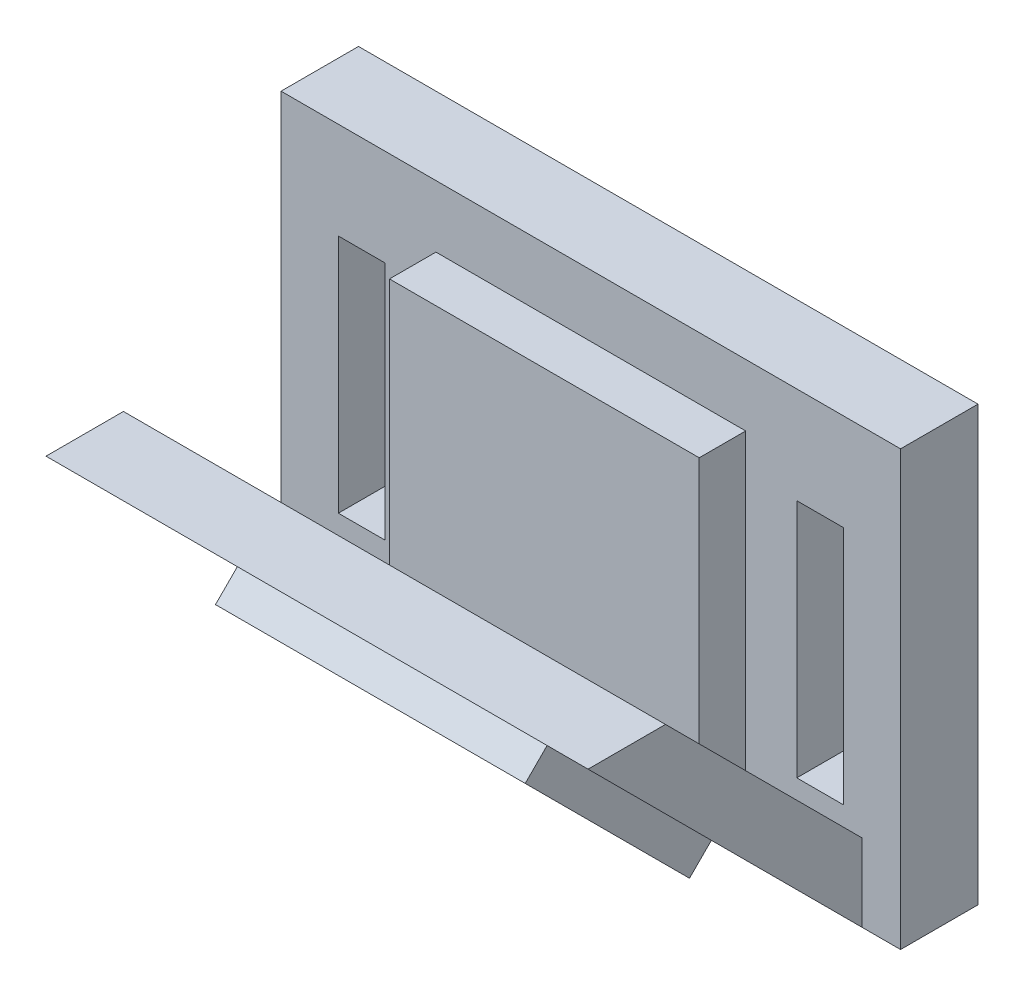
SolidWorks part; units mm, degrees
ref_plane "Alzado" through (0, 0, 0) normal (0, 0, 1) x (1, 0, 0)
ref_plane "Planta" through (0, 0, 0) normal (0, 1, 0) x (1, 0, 0)
ref_plane "Vista lateral" through (0, 0, 0) normal (1, 0, 0) x (0, 0, -1)
sketch "Croquis1" plane through (0, 0, 0) normal (0, 0, 1) x (1, 0, 0)
  line L0 (-39.1455, 0) -> (34.6181, 0) construction
  line L1 (-20, -14) -> (20, -14)
  line L2 (-20, -14) -> (-20, 14)
  line L3 (-20, 14) -> (20, 14)
  line L4 (20, -14) -> (20, 14)
  line L5 (-20, -14) -> (20, 14) construction
  line L6 (-20, 14) -> (20, -14) construction
  line L7 (0, 15.7634) -> (0, -15.7728) construction
  line L8 (13.3, -7.75) -> (16.3, -7.75)
  line L9 (13.3, -7.75) -> (13.3, 7.75)
  line L10 (13.3, 7.75) -> (16.3, 7.75)
  line L11 (16.3, -7.75) -> (16.3, 7.75)
  line L12 (13.3, -7.75) -> (16.3, 7.75) construction
  line L13 (13.3, 7.75) -> (16.3, -7.75) construction
  line L14 (-16.3, -7.75) -> (-13.3, -7.75)
  line L15 (-16.3, -7.75) -> (-16.3, 7.75)
  line L16 (-16.3, 7.75) -> (-13.3, 7.75)
  line L17 (-13.3, -7.75) -> (-13.3, 7.75)
  line L18 (-16.3, -7.75) -> (-13.3, 7.75) construction
  line L19 (-16.3, 7.75) -> (-13.3, -7.75) construction
  point P0 (0, 0)
  point P8 (14.8, 0)
  point P13 (-14.8, 0)
  dimension "D1" = 40
  dimension "D2" = 28
  dimension "D3" = 26.6
  dimension "D4" = 3
  dimension "D5" = 3
  dimension "D6" = 15.5
  dimension "D7" = 15.5
extrude "Saliente-Extruir1" add sketch "Croquis1" along normal mid plane 5
sketch "Croquis2" plane through (0, 0, 2.5) normal (0, 0, 1) x (1, 0, 0)
  line L1 (-10, -10) -> (10, -10)
  line L2 (-10, -10) -> (-10, 10)
  line L3 (-10, 10) -> (10, 10)
  line L4 (10, -10) -> (10, 10)
  line L5 (-10, -10) -> (10, 10) construction
  line L6 (-10, 10) -> (10, -10) construction
  point P0 (0, 0)
  dimension "D1" = 20
  dimension "D2" = 20
extrude "Saliente-Extruir2" add sketch "Croquis2" along normal blind 3
sketch "Croquis3" plane through (0, 0, 0) normal (1, 0, 0) x (0, 0, -1)
  line L0 (-2.5, -14) -> (-20.1777, 3.6777)
  line L1 (-20.1777, 3.6777) -> (-15.1777, 3.6777)
  line L2 (-15.1777, 3.6777) -> (-2.5, -9)
  line L3 (-2.5, -14) -> (-2.5, 14) construction
  line L4 (-2.5, -9) -> (-2.5, -14)
  line L5 (-2.5, -10) -> (-2.5, 10) construction
  point P9 (0, 0)
  dimension "D1" = 45
  dimension "D2" = 5
  dimension "D3" = 25
extrude "Saliente-Extruir3" add sketch "Croquis3" along normal mid plane 35
sketch "Croquis4" plane through (0, -8.25, 8.25) normal (0, -0.7071, 0.7071) x (1, 0, 0)
  line L0 (0, 18.4598) -> (0, -9.8466) construction
  line L2 (-10, 10) -> (10, 10)
  line L3 (-10, 10) -> (-10, -5)
  line L4 (-10, -5) -> (10, -5)
  line L5 (10, 10) -> (10, -5)
  dimension "D1" = 20
  dimension "D2" = 15
  dimension "D3" = 5
extrude "Saliente-Extruir4" add sketch "Croquis4" along normal blind 2
